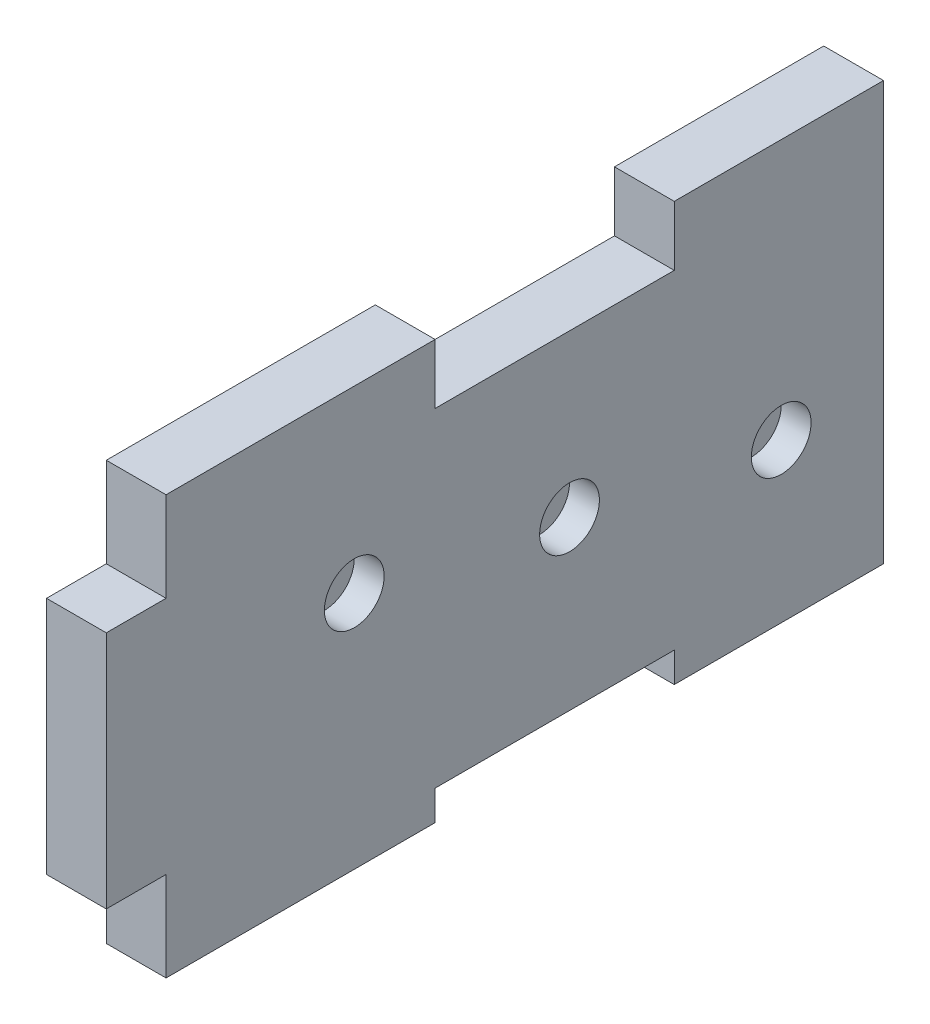
SolidWorks part; units mm, degrees
ref_plane "Front Plane" through (0, 0, 0) normal (0, 0, 1) x (1, 0, 0)
ref_plane "Top Plane" through (0, 0, 0) normal (0, 1, 0) x (1, 0, 0)
ref_plane "Right Plane" through (0, 0, 0) normal (1, 0, 0) x (0, 0, -1)
sketch "Sketch1" plane through (0, 0, 0) normal (1, 0, 0) x (0, 0, -1)
  line L1 (-130, 70) -> (0, 70)
  line L2 (-130, 70) -> (-130, 0)
  line L3 (-130, 0) -> (0, 0)
  line L4 (0, 70) -> (0, 0)
  line L5 (-130, 70) -> (-120, 70)
  line L6 (-130, 70) -> (-130, 55)
  line L7 (-130, 55) -> (-120, 55)
  line L8 (-120, 70) -> (-120, 55)
  line L9 (-130, 0) -> (-120, 0)
  line L10 (-130, 0) -> (-130, 15)
  line L11 (-130, 15) -> (-120, 15)
  line L12 (-120, 0) -> (-120, 15)
  line L13 (0, 70) -> (-10, 70)
  line L14 (0, 70) -> (0, 55)
  line L17 (0, 0) -> (-10, 0)
  line L18 (0, 0) -> (0, 15)
  line L21 (-75, 70) -> (-35, 70)
  line L22 (-75, 70) -> (-75, 60)
  line L23 (-75, 60) -> (-35, 60)
  line L24 (-35, 70) -> (-35, 60)
  line L25 (-75, 0) -> (-35, 0)
  line L26 (-75, 0) -> (-75, 5)
  line L27 (-75, 5) -> (-35, 5)
  line L28 (-35, 0) -> (-35, 5)
  dimension "D1" = 130
  dimension "D2" = 70
  dimension "D3" = 10
  dimension "D4" = 15
  dimension "D5" = 10
  dimension "D6" = 15
  dimension "D11" = 10
  dimension "D12" = 40
  dimension "D13" = 55
  dimension "D14" = 55
  dimension "D15" = 40
  dimension "D16" = 5
extrude "Boss-Extrude1" add sketch "Sketch1" along normal blind 5
sketch "Sketch2" plane through (5, 0, 0) normal (1, 0, 0) x (0, 0, -1)
  line L1 (-130, 55) -> (-130, 15) construction
  line L2 (-75, 5) -> (-35, 5) construction
  circle A0 centre (-88.52, 40) radius 5
  dimension "D3" = 10
  dimension "D1" = 35
  dimension "D2" = 41.48
sketch "Sketch5" plane through (0, 0, 0) normal (-1, 0, 0) x (0, 0, 1)
  line L0 (75, 5) -> (35, 5) construction
  line L1 (0, 70) -> (0, 0) construction
  line L3 (120, 70) -> (120, 55) construction
  circle A0 centre (52.52, 33) radius 5
  circle A1 centre (17.1117, 26.5) radius 5
  dimension "D1" = 10
  dimension "D4" = 10
  dimension "D6" = 17.1117
  dimension "D2" = 28
  dimension "D3" = 67.48
  dimension "D5" = 36
extrude "Cut-Extrude4" cut sketch "Sketch5" against normal blind 5 contours A1 | A0
extrude "Cut-Extrude5" cut sketch "Sketch2" against normal blind 5
sketch "Sketch6" plane through (0, 0, 0) normal (-1, 0, 0) x (0, 0, 1)
  line L40 (35, 0) -> (35, 5)
  line L41 (35, 5) -> (75, 5)
  line L42 (75, 5) -> (75, 0)
  line L43 (75, 0) -> (120, 0)
  line L44 (120, 0) -> (120, 15)
  line L45 (120, 15) -> (130, 15)
  line L46 (130, 15) -> (130, 55)
  line L47 (130, 55) -> (120, 55)
  line L48 (120, 55) -> (120, 70)
  line L49 (120, 70) -> (75, 70)
  line L50 (75, 70) -> (75, 60)
  line L51 (75, 60) -> (35, 60)
  line L52 (35, 60) -> (35, 70)
  line L53 (35, 70) -> (0, 70)
  line L56 (0, 70) -> (0, 0)
  line L59 (0, 0) -> (35, 0)
  line L60 (35, 0) -> (35, 5)
  line L61 (35, 5) -> (75, 5)
  line L62 (75, 5) -> (75, 0)
  line L63 (75, 0) -> (120, 0)
  line L64 (120, 0) -> (120, 15)
  line L65 (120, 15) -> (130, 15)
  line L66 (130, 15) -> (130, 55)
  line L67 (130, 55) -> (120, 55)
  line L68 (120, 55) -> (120, 70)
  line L69 (120, 70) -> (75, 70)
  line L70 (75, 70) -> (75, 60)
  line L71 (75, 60) -> (35, 60)
  line L72 (35, 60) -> (35, 70)
  line L73 (35, 70) -> (0, 70)
  line L76 (0, 70) -> (0, 0)
  line L79 (0, 0) -> (35, 0)
  dimension "D1" = 0
extrude "Boss-Extrude2" add sketch "Sketch6" along normal blind 5
